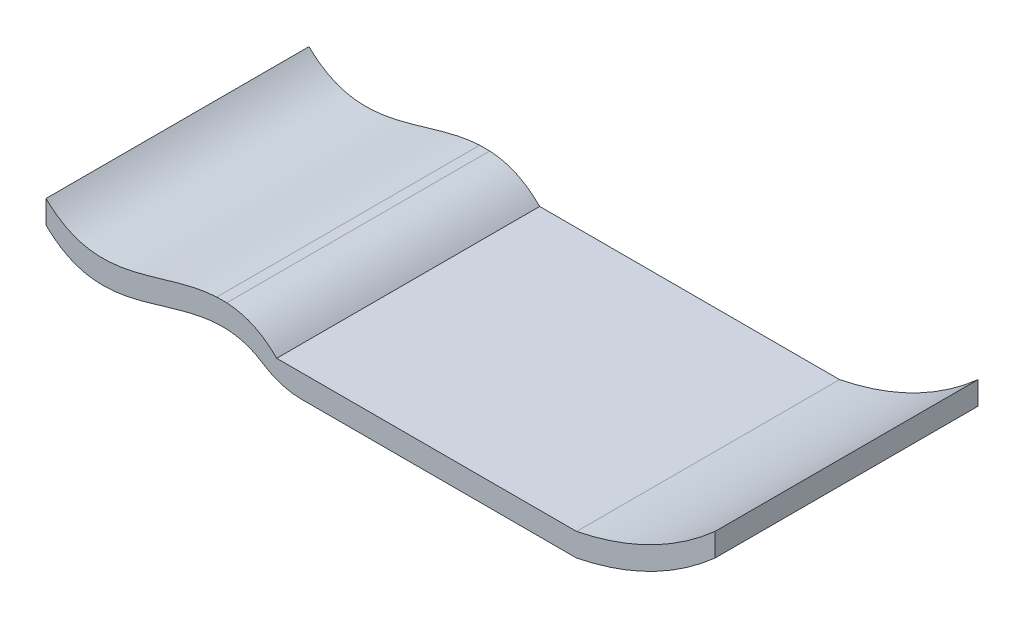
SolidWorks part; units mm, degrees
material "Aluminium 1050"
ref_plane "Front Plane" through (0, 0, 0) normal (0, 0, 1) x (1, 0, 0)
ref_plane "Top Plane" through (0, 0, 0) normal (0, 1, 0) x (1, 0, 0)
ref_plane "Right Plane" through (0, 0, 0) normal (1, 0, 0) x (0, 0, -1)
sketch "Sketch1" plane through (0, 0, 0) normal (0, 0, 1) x (1, 0, 0)
  line L0 (0, 0) -> (65, 0)
  line L1 (0, -5) -> (65, -5)
  line L2 (0, -5) -> (0, 0) construction
  line L3 (65, 0) -> (65, -5)
  line L4 (65, 0) -> (80, 0)
  line L5 (65, 5) -> (80, 5) construction
  line L6 (80, 5) -> (95, 5) construction
  line L7 (80, 10) -> (95, 10) construction
  line L8 (80, 15) -> (95, 15) construction
  line L9 (95, 15) -> (95, 10)
  line L10 (0, 0) -> (-20, 0) construction
  line L11 (0, 5) -> (-20, 5)
  line L12 (-20, 0) -> (-50, 0) construction
  line L13 (-50, 0) -> (-60, 0) construction
  line L14 (-50, 5) -> (-60, 5) construction
  line L15 (-20, 10) -> (-50, 10) construction
  line L16 (-50, 5) -> (-50, 0)
  line L17 (-20, -5) -> (-50, -5) construction
  spline S0 degree 2 poles (65, -5) (81.9734, -1.5349) (95, 10) knots 0 0 0 1 1 1
  spline S1 degree 2 poles (65, 0) (81.9734, 3.4651) (95, 15) knots 0 0 0 1 1 1
  spline S2 degree 3 poles (0, 0) (-15.0429, 15.1502) (-34.3268, -10.2469) (-50, 5) knots 0 0 0 0 1 1 1 1
  spline S3 degree 3 poles (0, -5) (-14.7624, 10.3483) (-34.2953, -15.4828) (-50, 0) knots 0 0 0 0 1 1 1 1
  dimension "D1" = 65
  dimension "D3" = 15
  dimension "D5" = 15
  dimension "D9" = 20
  dimension "D10" = 30
  dimension "D11" = 10
  dimension "D2" = 5
  dimension "D4" = 5
  dimension "D6" = 5
  dimension "D7" = 5
  dimension "D8" = 5
  dimension "D12" = 5
  dimension "D13" = 10
  dimension "D14" = 5
extrude "Boss-Extrude1" add sketch "Sketch1" along normal blind 57 contours L3 L0 L2 L1 | L3 S0 L4 | S1 L4 S0 L9
fillet "Fillet1" radius 15 1 edges at (0, -5, 28.5)
